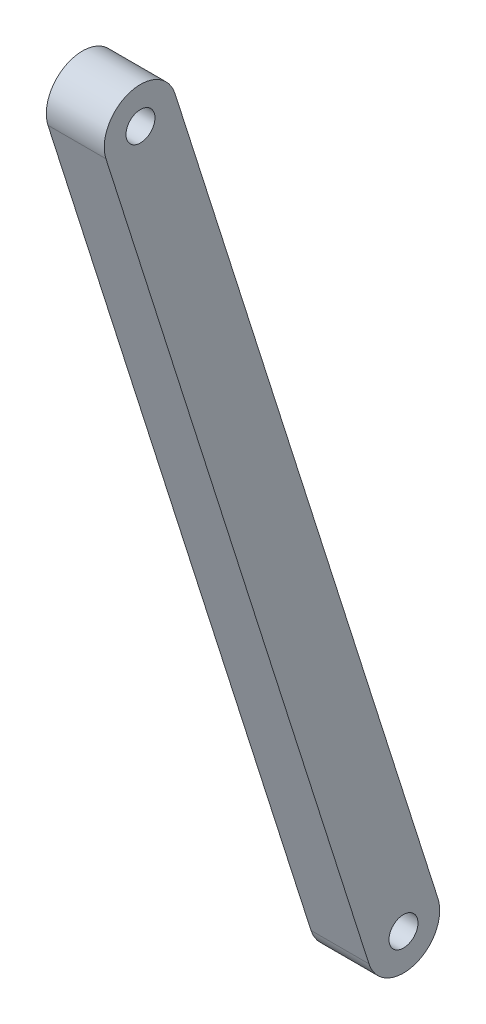
SolidWorks part; units mm, degrees
material "1060 合金"
ref_plane "前视基准面" through (0, 0, 0) normal (0, 0, 1) x (1, 0, 0)
ref_plane "上视基准面" through (0, 0, 0) normal (0, 1, 0) x (1, 0, 0)
ref_plane "右视基准面" through (0, 0, 0) normal (1, 0, 0) x (0, 0, -1)
sketch "草图1" plane through (0, 0, 0) normal (0, 0, 1) x (1, 0, 0)
  line L0 (0, -1.7341) -> (0, 48.3207) construction
  line L1 (-4, 125) -> (4, 125)
  line L2 (-6, 108.0718) -> (-6, 41.9282)
  line L4 (6, 108.0718) -> (6, 41.9282)
  line L5 (-6, 108.0718) -> (-10, 115)
  line L6 (-4, 125) -> (-4, 150)
  line L7 (-4, 150) -> (-10, 150)
  line L8 (-10, 115) -> (-10, 150)
  line L9 (10, 115) -> (10, 150)
  line L10 (4, 150) -> (10, 150)
  line L11 (4, 125) -> (4, 150)
  line L12 (6, 108.0718) -> (10, 115)
  line L13 (-4, 25) -> (4, 25)
  line L14 (-10, 35) -> (-6, 41.9282)
  line L15 (-10, 35) -> (-10, 0)
  line L16 (-10, 0) -> (-4, 0)
  line L17 (10, 35) -> (10, 0)
  line L18 (-4, 25) -> (-4, 0)
  line L19 (4, 25) -> (4, 0)
  line L20 (4, 0) -> (10, 0)
  line L21 (6, 41.9282) -> (10, 35)
  dimension "D1" = 12
  dimension "D2" = 8
  dimension "D3" = 8
  dimension "D4" = 25
  dimension "D5" = 35
  dimension "D6" = 20
  dimension "D7" = 25
  dimension "D8" = 35
  dimension "D9" = 150
  dimension "D10" = 30
  dimension "D11" = 30
  dimension "D12" = 30
sketch "连杆几何关系草图" plane through (0, 0, 0) normal (1, 0, 0) x (0, 0, -1)
  line L0 (0, 0) -> (20, 0)
  line L1 (20, 0) -> (72.9511, 28.2166)
  line L2 (72.9511, 28.2166) -> (134.5682, -5)
  line L3 (7.3409, -5) -> (163.0583, -5)
  line L4 (0, 0) -> (-15, 0)
  line L5 (-15, 0) -> (-15, 190.125)
  line L6 (-15, 190.125) -> (-7.3597, 166.3211)
  line L7 (72.9511, 28.2166) -> (28.939, 51.9428)
  line L8 (28.939, 51.9428) -> (-7.3597, 166.3211)
  line L9 (20, 0) -> (60.68, 44.1037)
  line L10 (60.68, 44.1037) -> (110.5682, -5)
  line L11 (25.0456, 79.1778) -> (8.7072, 198.0603)
  line L12 (8.7072, 198.0603) -> (-15, 190.125)
  line L13 (60.68, 44.1037) -> (25.0456, 79.1778)
  dimension "D1" = 20
  dimension "D2" = 15
  dimension "D3" = 60
  dimension "D4" = 70
  dimension "D5" = 5
  dimension "D6" = 190.125
  dimension "D7" = 25
  dimension "D8" = 50
  dimension "D9" = 24
  dimension "D10" = 120
sketch "草图4" plane through (0, 0, 0) normal (1, 0, 0) x (0, 0, -1)
  line L0 (-7.3597, 166.3211) -> (28.939, 51.9428) construction
  line L1 (-2.5939, 167.8336) -> (33.7047, 53.4552)
  line L2 (-12.1254, 164.8087) -> (24.1732, 50.4303)
  arc A0 (-2.5939, 167.8336) -> (-12.1254, 164.8087) centre (-7.3597, 166.3211) ccw
  arc A1 (24.1732, 50.4303) -> (33.7047, 53.4552) centre (28.939, 51.9428) ccw
  circle A2 centre (-7.3597, 166.3211) radius 2
  circle A3 centre (28.939, 51.9428) radius 2
  point P4 (10.7897, 109.1319)
  dimension "D1" = 4
  dimension "D2" = 5
extrude "凸台-拉伸2" add sketch "草图4" along normal mid plane 8
